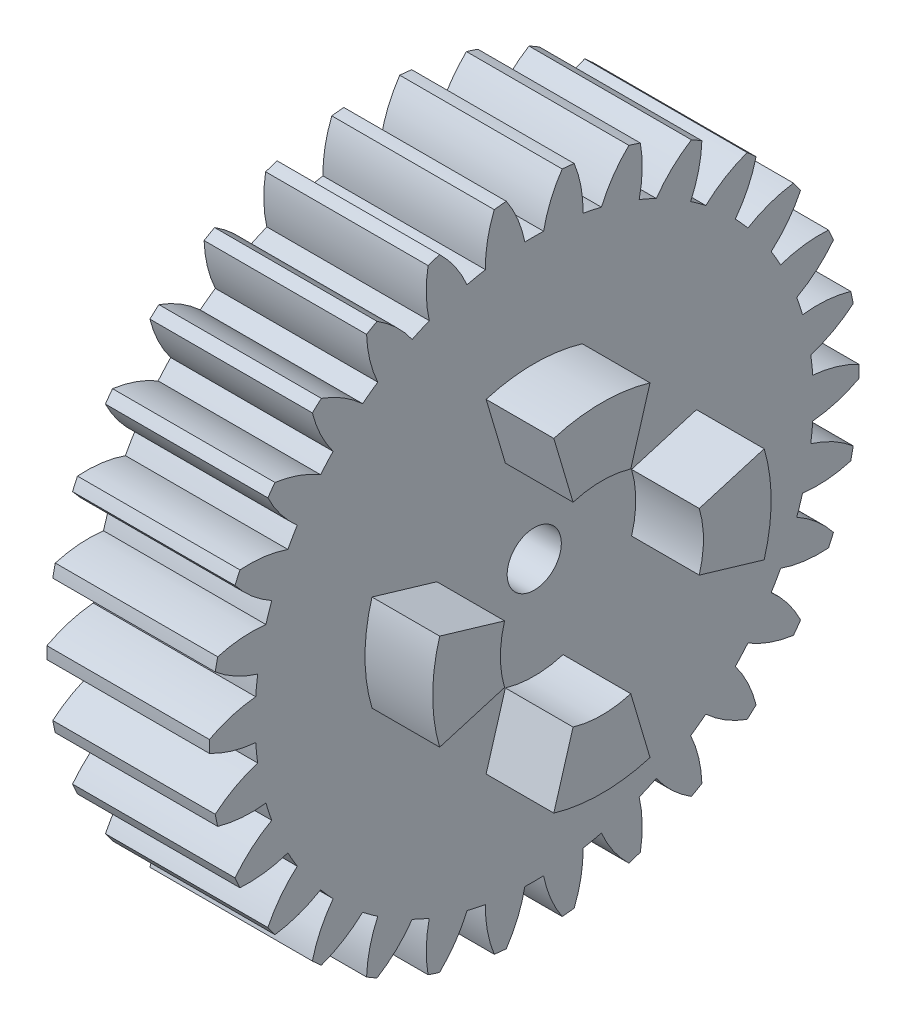
SolidWorks part; units mm, degrees
ref_plane "Plane1" through (0, 0, 0) normal (0, 0, 1) x (1, 0, 0)
ref_plane "Plane2" through (0, 0, 0) normal (0, 1, 0) x (1, 0, 0)
ref_plane "Plane3" through (0, 0, 0) normal (1, 0, 0) x (0, 0, -1)
sketch "HoldingSke" plane through (0, 0, 0) normal (0, 1, 0) x (1, 0, 0)
  line L0 (0, 0) -> (0.5774, -0.3333)
  line L1 (-15, 0) -> (100, 0) construction
  line L2 (0, 0) -> (-2.1039, 2.3779)
  line L3 (0, 0) -> (-11.863, 4.5341)
  line L4 (0, 0) -> (7.479, 4.318)
  line L5 (0, 0) -> (-46.8476, -17.4728)
  line L6 (0, 0) -> (-9.9476, -6.7116)
  line L7 (-2.1039, 2.3779) -> (8.6586, 51.2059)
  line L8 (-76.2, 54.61) -> (-75.5, 54.61)
  line L9 (-71.009, 38.7566) -> (-53.1078, 45.2721)
  line L10 (-76.2, 71.12) -> (104.1128, 71.12)
  line L11 (0, 0) -> (-12, 0)
  line L12 (-76.2, 101.6) -> (-76.147, 101.6)
  line L13 (24.9733, 27.94) -> (52.9518, 28.4284)
  line L14 (24.9733, 27.94) -> (24.9743, 27.94)
  line L15 (24.9733, 27.94) -> (100.4006, 29.5858)
  line L16 (-63.627, -1.5) -> (-12.827, -1.5)
  circle A0 centre (0, 0) radius 2
  circle A1 centre (0, 0) radius 20.624
  circle A2 centre (0, 0) radius 37.5
  circle A3 centre (0, 0) radius 2
  dimension "MHD" = 41.248
  dimension "Hub_dia" = 75
  dimension "Bore" = 4
  dimension "MBD" = 4
  dimension "Num_teeth" = 30
  dimension "Pitch" = 0.6667
  dimension "Overall_len" = 50
  dimension "Show_teeth" = 30
  dimension "Thickness" = 12
  dimension "OAL" = 50.0001
  dimension "T_dim" = 0.7
  dimension "Ap" = 20
  dimension "H" = 19.05
  dimension "Pitch_radius" = 180.3128
  dimension "Width" = 12
  dimension "Backlash" = 0.053
  dimension "Addendum_fac" = 1
  dimension "Dedendum_fac" = 1.25
  dimension "Clearance_fac" = 0.25
  dimension "Dedendum_add" = 0.001
  dimension "Module" = 1.5
sketch "BasProSke" plane through (0, 0, 0) normal (0, 1, 0) x (1, 0, 0)
  line L0 (-10, 0) -> (60, 0) construction
  line L1 (0, 0) -> (0, 24)
  line L2 (0, 0) -> (12, 0)
  line L3 (12, 0) -> (12, 24)
  line L4 (12, 24) -> (0, 24)
  dimension "Thickness" = 12
  dimension "Diameter" = 48
revolve "Base-Revolve" add sketch "BasProSke" angle 360 about L0
sketch "TooCutSke" plane through (0, 0, 0) normal (1, 0, 0) x (0, 0, -1)
  line L1 (0, 0) -> (0, 107) construction
  line L2 (0, 0) -> (-1.2703, 22.4641) construction
  line L3 (0, 0) -> (-4.6983, 44.7014) construction
  line L4 (-1.2703, 22.4641) -> (-2.3492, 22.3507) construction
  arc A0 (0.6933, 20.6123) -> (-0.6933, 20.6123) centre (0, 0) ccw
  arc A1 (2.0805, 23.9351) -> (-2.0805, 23.9351) centre (0, 0) ccw
  circle A2 centre (0, 0) radius 22.5 construction
  circle A3 centre (0, 0) radius 21.1431 construction
  arc A4 (-0.6933, 20.6123) -> (-2.0805, 23.9351) centre (-9.5243, 18.8764) ccw
  arc A5 (2.0805, 23.9351) -> (0.6933, 20.6123) centre (9.5243, 18.8764) ccw
  dimension "Root_dia" = 41.248
  dimension "Overcut_dia" = 48.0508
  dimension "Pitch_dia" = 45
  dimension "Base_dia" = 42.2862
  dimension "Flank_rad" = 9
  dimension "Half_ang" = 6
  dimension "Half_CT" = 1.0848
extrude "ToothCut" cut sketch "TooCutSke" along normal through all
fillet "Breaks" [suppressed] radius 0.03
fillet "RootFillets" [suppressed] radius 0.376
pattern_circular "TeethCuts" count 30 every 12 about axis through (-10, 0, 0) along (1, 0, 0) of "ToothCut", "RootFillets", "Breaks"
sketch "HubNeaOneSke" plane through (0, 0, 0) normal (-1, 0, 0) x (0, 0, 1)
  circle A0 centre (0, 0) radius 20.624
  dimension "Diameter" = 41.248
extrude "HubNearOne" [suppressed] add sketch "HubNeaOneSke" along normal blind 38.0001
sketch "HubNeaBotSke" plane through (0, 0, 0) normal (-1, 0, 0) x (0, 0, 1)
  circle A0 centre (0, 0) radius 20.624
  dimension "Diameter" = 41.248
extrude "HubNearBoth" [suppressed] add sketch "HubNeaBotSke" along normal blind 19
ref_plane "FarPln" through (12, 0, 0) normal (1, 0, 0) x (0, 0, -1)
sketch "HubFarSke" plane through (12, 0, 0) normal (1, 0, 0) x (0, 0, -1)
  circle A0 centre (0, 0) radius 20.624
  dimension "Diameter" = 41.248
extrude "HubFar" [suppressed] add sketch "HubFarSke" along normal blind 19
sketch "BorSke" plane through (0, 0, 0) normal (1, 0, 0) x (0, 0, -1)
  circle A0 centre (0, 0) radius 2
  dimension "Diameter" = 4
extrude "Bore" cut sketch "BorSke" along normal mid plane 100.0001
sketch "KeySke" plane through (0, 0, 0) normal (1, 0, 0) x (0, 0, -1)
  line L0 (-0.8, 0) -> (-0.8, 2.7)
  line L1 (-0.8, 2.7) -> (0.8, 2.7)
  line L2 (0.8, 2.7) -> (0.8, 0)
  line L3 (0, 0) -> (0, 34) construction
  line L4 (-0.8, 0) -> (0.8, 0)
  dimension "Offset" = 2.7
  dimension "Width" = 1.6
extrude "Keyway" [suppressed] cut sketch "KeySke" along normal mid plane 100.0001
pattern_circular "Keyway2" [suppressed] count 2 every 90 about axis through (-10, 0, 0) along (1, 0, 0)
sketch "草图1" plane through (12, 0, 0) normal (1, 0, 0) x (0, 0, -1)
  line L0 (-2.1318, 7.1906) -> (-3.553, 11.9844)
  line L1 (0, 7.5) -> (0, 12.5) construction
  line L2 (2.1318, 7.1906) -> (3.553, 11.9844)
  line L3 (7.1906, 2.1318) -> (11.9844, 3.553)
  line L4 (7.1906, -2.1318) -> (11.9844, -3.553)
  line L5 (2.1318, -7.1906) -> (3.553, -11.9844)
  line L6 (-2.1318, -7.1906) -> (-3.553, -11.9844)
  line L7 (-7.1906, -2.1318) -> (-11.9844, -3.553)
  line L8 (-7.1906, 2.1318) -> (-11.9844, 3.553)
  arc A0 (2.1318, 7.1906) -> (-2.1318, 7.1906) centre (0, 0) ccw
  arc A1 (3.553, 11.9844) -> (-3.553, 11.9844) centre (0, 0) ccw
  arc A2 (-3.553, 11.9844) -> (3.553, 11.9844) centre (0, 0) ccw construction
  arc A3 (-2.1318, 7.1906) -> (2.1318, 7.1906) centre (0, 0) ccw construction
  arc A4 (11.9844, -3.553) -> (11.9844, 3.553) centre (0, 0) ccw
  arc A5 (7.1906, -2.1318) -> (7.1906, 2.1318) centre (0, 0) ccw
  arc A6 (-3.553, -11.9844) -> (3.553, -11.9844) centre (0, 0) ccw
  arc A7 (-2.1318, -7.1906) -> (2.1318, -7.1906) centre (0, 0) ccw
  arc A8 (-11.9844, 3.553) -> (-11.9844, -3.553) centre (0, 0) ccw
  arc A9 (-7.1906, 2.1318) -> (-7.1906, -2.1318) centre (0, 0) ccw
  point P23 (0, 0)
  dimension "D1" = 25
  dimension "D2" = 15
  dimension "D3" = 4
extrude "凸台-拉伸1" add sketch "草图1" along normal blind 5
ref_plane "基准面1" through (6, 0, 0) normal (1, 0, 0) x (0, 0, -1)
equation "' \"Module@HoldingSke\" = 6.35"
equation "' \"Num_teeth@HoldingSke\" = 12"
equation "' \"Ap@HoldingSke\" =  20"
equation "' \"Ap@HoldingSke\" = 20"
equation "' \"Width@HoldingSke\" = 0.5 * 25.4"
equation "' \"Hub_dia@HoldingSke\"= 1 * 25.4"
equation "' \"Hub_dia@HoldingSke\" = 1 * 25.4"
equation "' \"Overall_len@HoldingSke\" = 1.0 * 25.4"
equation "' \"Bore@HoldingSke\" = 0.75 * 25.4"
equation "' \"T_dim@HoldingSke\" = 0.1 * 25.4"
equation "' \"Width@KeySke\" = 0.25 * 25.4"
equation "' \"Show_teeth@HoldingSke\" = 13"
equation "' \"Backlash@HoldingSke\" = 0.009 * 25.4"
equation "' \"Addendum_fac@HoldingSke\" = 1.0"
equation "' \"Dedendum_fac@HoldingSke\" = 1.25"
equation "' \"Dedendum_add@HoldingSke\" = 0.00005 * 25.4"
equation "' \"Clearance_fac@HoldingSke\" = 0.25"
equation "\"Pitch@HoldingSke\" = 1 / \"Module@HoldingSke\""
equation "\"Overcut_dia@TooCutSke\" = (\"Num_teeth@HoldingSke\" + 2 * \"Addendum_fac@HoldingSke\") / \"Pitch@HoldingSke\" + 0.002 * 25.4"
equation "\"Pitch_dia@TooCutSke\" = \"Num_teeth@HoldingSke\" / \"Pitch@HoldingSke\""
equation "\"Base_dia@TooCutSke\" = \"Num_teeth@HoldingSke\" / \"Pitch@HoldingSke\" * cos((\"Ap@HoldingSke\"  * 3.14159265 / 180))"
equation "\"Root_dia@TooCutSke\" = (\"Num_teeth@HoldingSke\" + 2) / \"Pitch@HoldingSke\" - 2 * (\"Addendum_fac@HoldingSke\" + \"Dedendum_fac@HoldingSke\") / \"Pitch@HoldingSke\" - \"Dedendum_add@HoldingSke\" * 2"
equation "\"Half_ang@TooCutSke\" = 180 / \"Num_teeth@HoldingSke\""
equation "\"Half_CT@TooCutSke\" = \"Num_teeth@HoldingSke\" / \"Pitch@HoldingSke\" * sin((3.14159265 / 2 / \"Num_teeth@HoldingSke\")) / 2 - 7 * \"Backlash@HoldingSke\" / 4"
equation "\"Flank_rad@TooCutSke\" = \"Num_teeth@HoldingSke\" / \"Pitch@HoldingSke\" / 5"
equation "\"Radius@RootFillets\" = \"Clearance_fac@HoldingSke\" / \"Pitch@HoldingSke\" + \"Dedendum_add@HoldingSke\""
equation "\"Break_rad@Breaks\" = 0.02 / \"Pitch@HoldingSke\""
equation "\"Thickness@HoldingSke\" = \"Width@HoldingSke\""
equation "\"OAL@HoldingSke\" = \"Thickness@HoldingSke\""
equation "\"MHD@HoldingSke\" = (\"Num_teeth@HoldingSke\" + 2) / \"Pitch@HoldingSke\" - 2 * (\"Addendum_fac@HoldingSke\" + \"Dedendum_fac@HoldingSke\")  / \"Pitch@HoldingSke\" - \"Dedendum_add@HoldingSke\" * 2"
equation "\"MBD@HoldingSke\" = (\"Num_teeth@HoldingSke\" + 2) / \"Pitch@HoldingSke\" - 2 * (\"Addendum_fac@HoldingSke\" + \"Dedendum_fac@HoldingSke\")  / \"Pitch@HoldingSke\" - \"Dedendum_add@HoldingSke\" * 2 - 0.002 * 25.4"
equation "\"MHD@HoldingSke\" = ((sgn( \"MHD@HoldingSke\" - \"Hub_dia@HoldingSke\" )-1)*( \"MHD@HoldingSke\" - \"Hub_dia@HoldingSke\" ))/-2+ \"Hub_dia@HoldingSke\""
equation "\"MBD@HoldingSke\" = ((sgn( \"MBD@HoldingSke\" - \"Bore@HoldingSke\" )-1)*( \"MBD@HoldingSke\" - \"Bore@HoldingSke\" ))/-2+ \"Bore@HoldingSke\""
equation "\"OAL@HoldingSke\" = ((sgn( \"OAL@HoldingSke\" - \"Overall_len@HoldingSke\" )+1)*( \"OAL@HoldingSke\" - \"Overall_len@HoldingSke\" ))/2 + \"Overall_len@HoldingSke\" + 0.000002 * 25.4"
equation "\"Num_teeth@TeethCuts\" = int( \"Show_teeth@HoldingSke\" ) + 1"
equation "\"Num_teeth@TeethCuts\" = ((sgn( \"Num_teeth@TeethCuts\" - \"Num_teeth@HoldingSke\" )-1)*( \"Num_teeth@TeethCuts\" - \"Num_teeth@HoldingSke\" ))/-2+ \"Num_teeth@HoldingSke\""
equation "\"Num_teeth@TeethCuts\" = ((sgn( \"Num_teeth@TeethCuts\" - 2.0)+1)*( \"Num_teeth@TeethCuts\" - 2.0))/2 +2.0"
equation "\"Angle@TeethCuts\" = 360.0 / \"Num_teeth@HoldingSke\""
equation "\"Diameter@BasProSke\" = (\"Num_teeth@HoldingSke\" + 2 * \"Addendum_fac@HoldingSke\") / \"Pitch@HoldingSke\""
equation "\"Thickness@BasProSke\"  = \"Thickness@HoldingSke\""
equation "' \"Fillet_rad@BasProSke\" =  \"Thickness@HoldingSke\" * 0.05"
equation "' \"Fillet_rad@BasProSke\" = \"Thickness@HoldingSke\" * 0.05"
equation "\"MHD@HoldingSke\" = ((sgn( \"MHD@HoldingSke\" - \"Root_dia@TooCutSke\" )-1)*( \"MHD@HoldingSke\" - \"Root_dia@TooCutSke\" ))/-2+ \"Root_dia@TooCutSke\""
equation "\"Diameter@HubNeaOneSke\" = \"MHD@HoldingSke\""
equation "\"Length@HubNearOne\" = \"OAL@HoldingSke\" - \"Thickness@BasProSke\""
equation "\"Diameter@HubNeaBotSke\" = \"MHD@HoldingSke\""
equation "\"Length@HubNearBoth\" = ( \"OAL@HoldingSke\" - \"Thickness@BasProSke\" ) / 2.0"
equation "\"Thickness@FarPln\" = \"Thickness@BasProSke\""
equation "\"Diameter@HubFarSke\" = \"MHD@HoldingSke\""
equation "\"Length@HubFar\" = ( \"OAL@HoldingSke\" - \"Thickness@BasProSke\" ) / 2.0"
equation "\"Diameter@BorSke\" = \"MBD@HoldingSke\""
equation "\"D1@Bore\" = \"OAL@HoldingSke\" * 2.0"
equation "\"D1@Keyway\" = \"OAL@HoldingSke\" * 2.0"
equation "\"Offset@KeySke\" = \"T_dim@HoldingSke\" + \"MBD@HoldingSke\" / 2.0"
